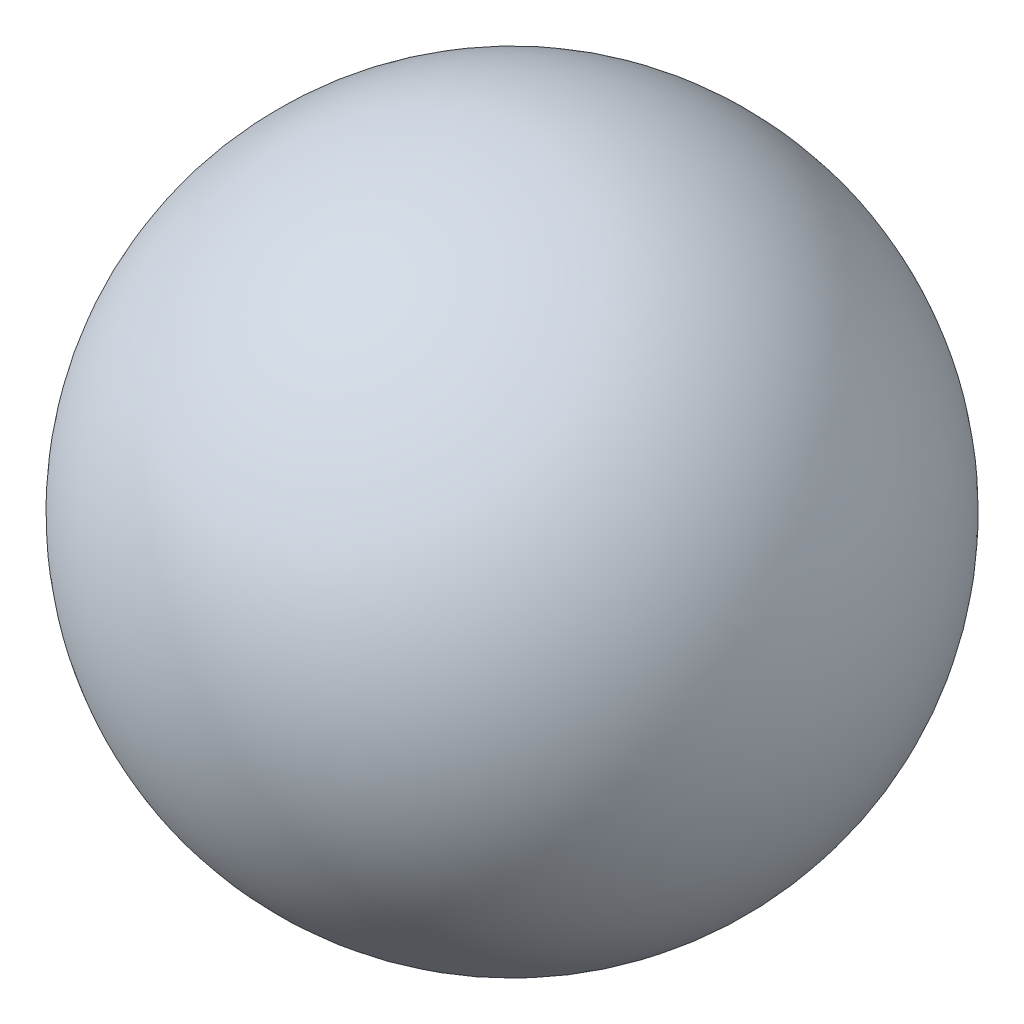
SolidWorks part; units mm, degrees
ref_plane "Front Plane" through (0, 0, 0) normal (0, 0, 1) x (1, 0, 0)
ref_plane "Top Plane" through (0, 0, 0) normal (0, 1, 0) x (1, 0, 0)
ref_plane "Right Plane" through (0, 0, 0) normal (1, 0, 0) x (0, 0, -1)
sketch "Sketch2" plane through (0, 0, 0) normal (0, 1, 0) x (1, 0, 0)
  line L0 (0, 0) -> (0, 74) construction
  line L1 (0, 0) -> (0, 74)
  arc A0 (0, 74) -> (0, 0) centre (0, 37) ccw
  dimension "D2" = 37
  dimension "D1" = 74
revolve "Revolve1" add sketch "Sketch2" angle 360 about L0
